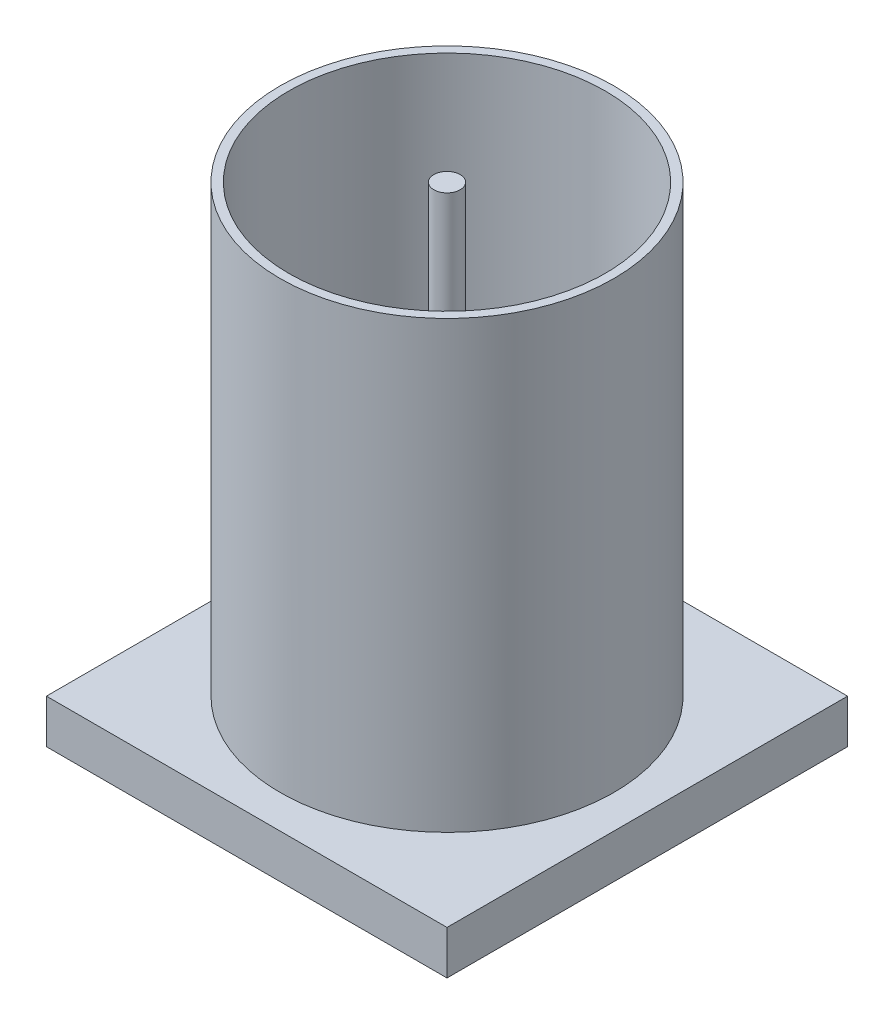
SolidWorks part; units mm, degrees
ref_plane "Front Plane" through (0, 0, 0) normal (0, 0, 1) x (1, 0, 0)
ref_plane "Top Plane" through (0, 0, 0) normal (0, 1, 0) x (1, 0, 0)
ref_plane "Right Plane" through (0, 0, 0) normal (1, 0, 0) x (0, 0, -1)
sketch "Sketch2" plane through (0, 0, 0) normal (0, 1, 0) x (1, 0, 0)
  line L1 (-2.286, -2.286) -> (2.286, -2.286)
  line L2 (-2.286, -2.286) -> (-2.286, 2.286)
  line L3 (-2.286, 2.286) -> (2.286, 2.286)
  line L4 (2.286, -2.286) -> (2.286, 2.286)
  line L5 (-2.286, -2.286) -> (2.286, 2.286) construction
  line L6 (-2.286, 2.286) -> (2.286, -2.286) construction
  point P0 (0, 0)
  dimension "D1" = 4.572
  dimension "D2" = 4.572
extrude "Boss-Extrude1" add sketch "Sketch2" along normal blind 0.5
sketch "Sketch3" plane through (0, 0.5, 0) normal (0, 1, 0) x (1, 0, 0)
  circle A0 centre (0, 0) radius 1.905
extrude "Boss-Extrude2" add sketch "Sketch3" along normal blind 5.08
shell "Shell10" thickness 0.1
sketch "Sketch7" plane through (0, 0.5, 0) normal (0, 1, 0) x (1, 0, 0)
  circle A0 centre (0, 0) radius 0.15
  dimension "D1" = 0.3
extrude "Boss-Extrude3" add sketch "Sketch7" along normal blind 5.08 separate body
ref_plane "Plane3" through (-2.286, 0.5, 2.286) normal (0, -1, 0) x (-1, 0, 0)
